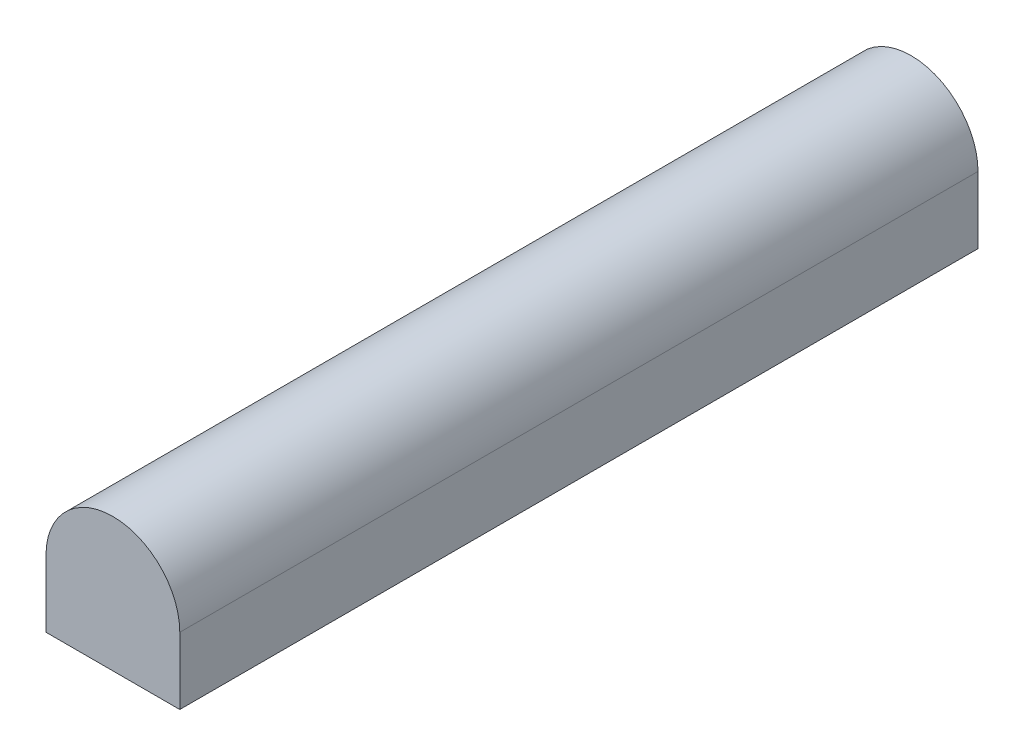
SolidWorks part; units mm, degrees
ref_plane "Alzado" through (0, 0, 0) normal (0, 0, 1) x (1, 0, 0)
ref_plane "Planta" through (0, 0, 0) normal (0, 1, 0) x (1, 0, 0)
ref_plane "Vista lateral" through (0, 0, 0) normal (1, 0, 0) x (0, 0, -1)
sketch "Croquis2" plane through (0, 0, 0) normal (0, 0, 1) x (1, 0, 0)
  line L1 (-14.2268, -9.5361) -> (15.7732, -9.5361)
  line L2 (-14.2268, -9.5361) -> (-14.2268, 5.4639)
  line L4 (15.7732, -9.5361) -> (15.7732, 5.4639)
  arc A0 (15.7732, 5.4639) -> (-14.2268, 5.4639) centre (0.7732, 5.4639) ccw
  point P5 (0.7732, 20.4639)
  dimension "D1" = 30
  dimension "D2" = 15
  dimension "D3" = 30
extrude "Saliente-Extruir1" add sketch "Croquis2" along normal mid plane 179
sketch "Croquis3" plane through (0, -9.5361, 0) normal (0, -1, 0) x (1, 0, 0)
  line L0 (0, -55) -> (0, 55) construction
  line L1 (-14.2268, 89.5) -> (15.7732, 89.5) construction
  line L2 (-14.2268, -89.5) -> (15.7732, -89.5) construction
  circle A0 centre (0, 69.5) radius 6
  circle A1 centre (0, -69.5) radius 6
  dimension "D3" = 12
  dimension "D4" = 12
  dimension "D1" = 20
  dimension "D2" = 20
extrude "Cortar-Extruir1" cut sketch "Croquis3" against normal blind 15
